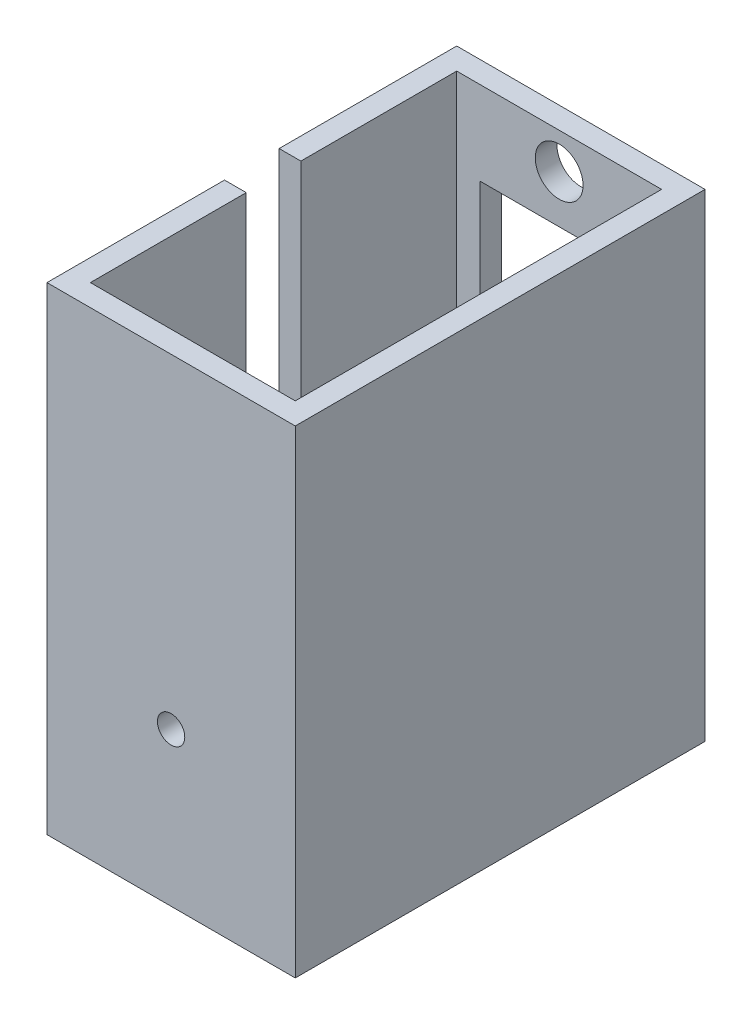
SolidWorks part; units mm, degrees
material "6061 Alloy"
ref_plane "Front Plane" through (0, 0, 0) normal (0, 0, 1) x (1, 0, 0)
ref_plane "Top Plane" through (0, 0, 0) normal (0, 1, 0) x (1, 0, 0)
ref_plane "Right Plane" through (0, 0, 0) normal (1, 0, 0) x (0, 0, -1)
sketch "Sketch1" plane through (0, 0, 0) normal (0, 1, 0) x (1, 0, 0)
  line L0 (0, -13) -> (1.59, -13)
  line L1 (0, 0) -> (18.18, 0)
  line L2 (0, 0) -> (0, -13)
  line L3 (0, -30) -> (18.18, -30)
  line L4 (18.18, 0) -> (18.18, -30)
  line L5 (1.59, -1.59) -> (16.59, -1.59)
  line L6 (1.59, -1.59) -> (1.59, -13)
  line L7 (1.59, -28.41) -> (16.59, -28.41)
  line L8 (16.59, -1.59) -> (16.59, -28.41)
  line L9 (0, -17) -> (1.59, -17)
  line L10 (1.59, -17) -> (1.59, -28.41)
  line L11 (0, -17) -> (0, -30)
  point P13 (9.09, -30)
  dimension "D1" = 1.59
  dimension "D2" = 1.59
  dimension "D3" = 1.59
  dimension "D4" = 1.59
  dimension "D5" = 30
  dimension "D6" = 13
  dimension "D7" = 13
  dimension "D8" = 15
extrude "Boss-Extrude1" add sketch "Sketch1" along normal blind 35
sketch "Sketch2" plane through (0, 0, 0) normal (0, 0, -1) x (-1, 0, 0)
  line L0 (0, 35) -> (0, 0) construction
  line L1 (-3.29, 28.875) -> (-14.89, 28.875)
  line L2 (-3.29, 28.875) -> (-3.29, 6.125)
  line L3 (-3.29, 6.125) -> (-14.89, 6.125)
  line L4 (-14.89, 28.875) -> (-14.89, 6.125)
  line L5 (-3.29, 28.875) -> (-14.89, 6.125) construction
  line L6 (-3.29, 6.125) -> (-14.89, 28.875) construction
  line L7 (-18.18, 0) -> (0, 0) construction
  circle A0 centre (-9.09, 32.375) radius 1.75
  circle A1 centre (-9.09, 2.625) radius 1.75
  point P0 (-9.09, 17.5)
  point P7 (0, 17.5)
  point P10 (-9.09, 0)
  point P11 (-9.09, 6.125)
  dimension "D5" = 3.5
  dimension "D1" = 11.6
  dimension "D2" = 22.75
  dimension "D3" = 3.5
  dimension "D4" = 3.5
extrude "Cut-Extrude1" cut sketch "Sketch2" against normal up to surface (1.59 mm away) up to face at (9.09, 17.5, 1.59)
sketch "Sketch3" plane through (0, 0, 30) normal (0, 0, 1) x (1, 0, 0)
  line L0 (0, 0) -> (18.18, 0) construction
  line L1 (0, 35) -> (0, 0) construction
  circle A0 centre (9.09, 17.5) radius 1
  point P2 (0, 0)
  point P5 (9.09, 0)
  point P8 (0, 17.5)
  dimension "D1" = 2
extrude "Cut-Extrude2" [suppressed] cut sketch "Sketch3" against normal blind 4
sketch "Sketch4" plane through (0, 0, 0) normal (-1, 0, 0) x (0, 0, 1)
  line L0 (0, 0) -> (13, 0) construction
  line L1 (17, 0) -> (30, 0) construction
  circle A0 centre (6.5, 11.22) radius 1.25
  circle A1 centre (23.5, 11.22) radius 1.25
  point P4 (0, 0)
  point P7 (6.5, 0)
  point P8 (0, 0)
  point P11 (23.5, 0)
  dimension "D2" = 2.5
  dimension "D1" = 11.22
extrude "Cut-Extrude3" cut sketch "Sketch4" against normal blind 4
sketch "Sketch5" plane through (0, 0, 30) normal (0, 0, 1) x (1, 0, 0)
  line L0 (0, 0) -> (18.18, 0) construction
  circle A0 centre (9.09, 11.22) radius 1
  point P2 (0, 0)
  point P5 (9.09, 0)
  dimension "D2" = 2
  dimension "D1" = 11.22
extrude "Cut-Extrude4" cut sketch "Sketch5" against normal blind 4
